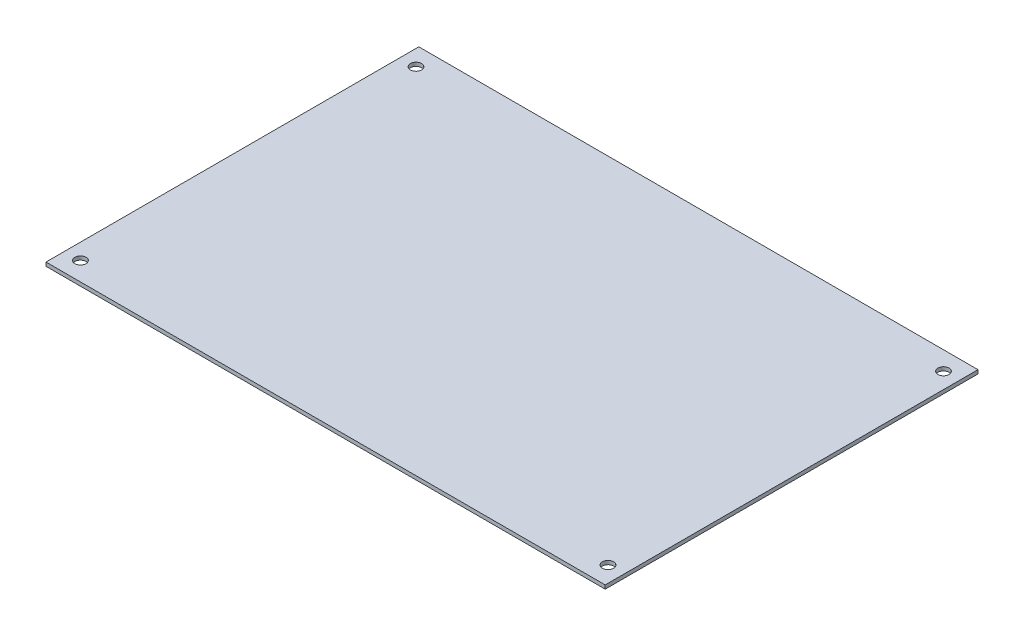
SolidWorks part; units mm, degrees
ref_plane "前视基准面" through (0, 0, 0) normal (0, 0, 1) x (1, 0, 0)
ref_plane "上视基准面" through (0, 0, 0) normal (0, 1, 0) x (1, 0, 0)
ref_plane "右视基准面" through (0, 0, 0) normal (1, 0, 0) x (0, 0, -1)
sketch "草图1" plane through (0, 0, 0) normal (0, 1, 0) x (1, 0, 0)
  line L1 (75, -50) -> (-75, -50)
  line L2 (75, -50) -> (75, 50)
  line L3 (75, 50) -> (-75, 50)
  line L4 (-75, -50) -> (-75, 50)
  line L5 (0, 50) -> (0, -50) construction
  line L6 (75, 0) -> (-75, 0) construction
  point P0 (0, 0)
extrude "凸台-拉伸1" add sketch "草图1" against normal mid plane 1
sketch "草图2" plane through (0, 0, 0) normal (0, 1, 0) x (1, 0, 0)
  line L1 (70.75, -45) -> (-70.75, -45)
  line L2 (70.75, -45) -> (70.75, 45)
  line L3 (70.75, 45) -> (-70.75, 45)
  line L4 (-70.75, -45) -> (-70.75, 45)
  line L5 (0, 45) -> (0, -45) construction
  line L6 (70.75, 0) -> (-70.75, 0) construction
  circle A0 centre (-70.75, 45) radius 1.5
  circle A1 centre (70.75, 45) radius 1.5
  circle A2 centre (-70.75, -45) radius 1.5
  circle A3 centre (70.75, -45) radius 1.5
  point P0 (0, 0)
extrude "切除-拉伸1" cut sketch "草图2" against normal through all both and the other way through all contours A0 | A2 | A1 | A3
